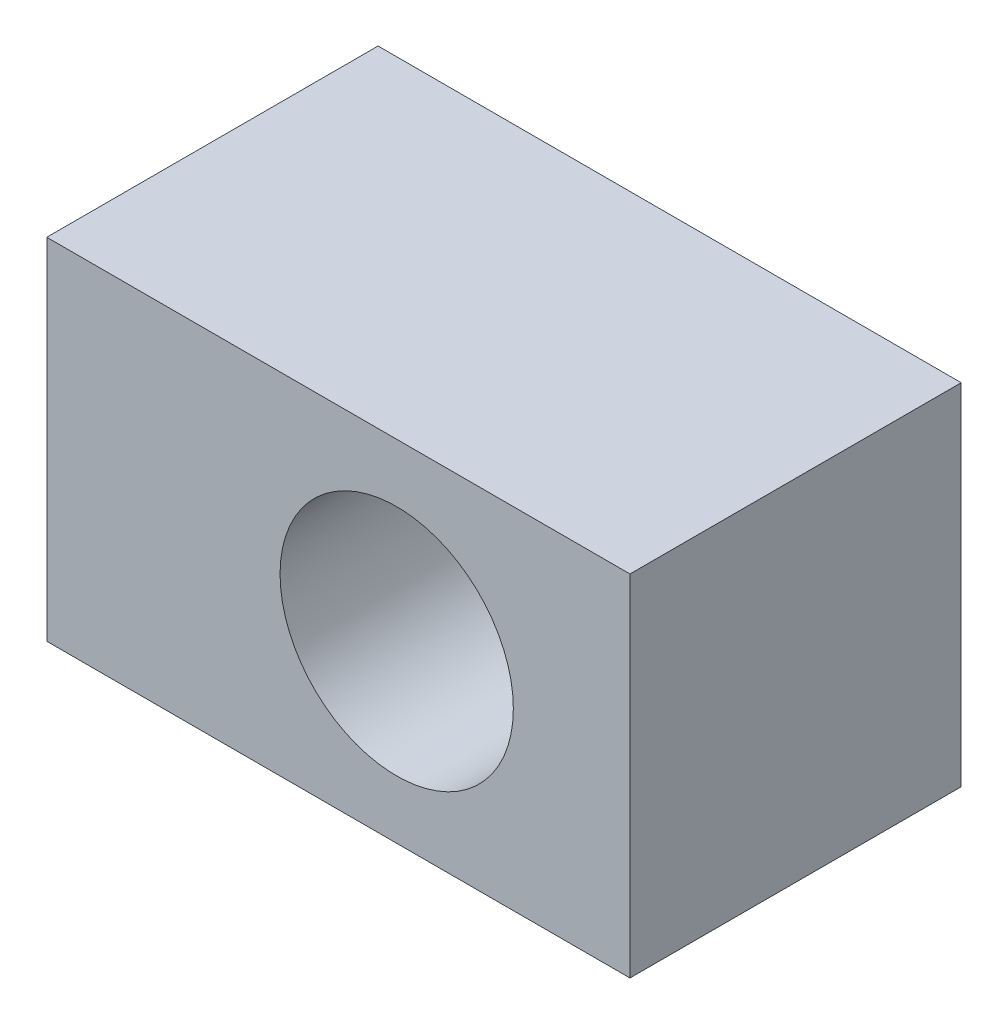
SolidWorks part; units mm, degrees
ref_plane "Front Plane" through (0, 0, 0) normal (0, 0, 1) x (1, 0, 0)
ref_plane "Top Plane" through (0, 0, 0) normal (0, 1, 0) x (1, 0, 0)
ref_plane "Right Plane" through (0, 0, 0) normal (1, 0, 0) x (0, 0, -1)
sketch "Sketch1" plane through (0, 0, 0) normal (0, 0, 1) x (1, 0, 0)
  line L1 (0, 76.2) -> (127, 76.2)
  line L2 (0, 76.2) -> (0, 0)
  line L3 (0, 0) -> (127, 0)
  line L4 (127, 76.2) -> (127, 0)
  point P4 (-30.6143, -32.4907)
  point P5 (0, 0)
  point P7 (127, 62.5124)
  dimension "D1" = 127
  dimension "D2" = 76.2
extrude "Boss-Extrude1" add sketch "Sketch1" along normal blind 72.136
sketch "Sketch2" plane through (0, 0, 72.136) normal (0, 0, 1) x (1, 0, 0)
  line L0 (0, 76.2) -> (0, 0) construction
  line L1 (0, 0) -> (127, 0) construction
  circle A0 centre (76.2, 38.1) radius 25.4
  dimension "D2" = 38.1
  dimension "D3" = 50.8
  dimension "D1" = 76.2
extrude "Cut-Extrude1" cut sketch "Sketch2" against normal through all
